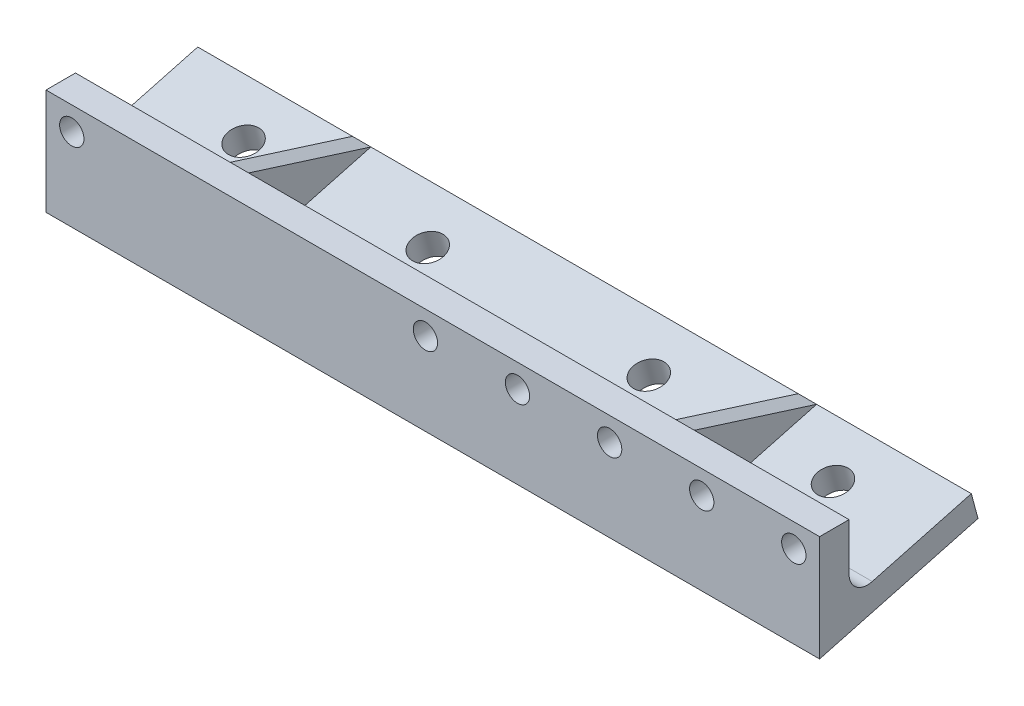
SolidWorks part; units mm, degrees
other "标注1"
sketch "草图25" plane through (-52, 30, -95) normal (-0.4172, 0.7166, -0.559) x (-0.8994, -0.2372, 0.3671)
other "标注2"
sketch "草图26" plane through (-52, 30, -95) normal (-0.4172, 0.7166, -0.559) x (-0.8994, -0.2372, 0.3671)
material "1060 合金"
ref_plane "前视基准面" through (0, 0, 0) normal (0, 0, 1) x (1, 0, 0)
ref_plane "上视基准面" through (0, 0, 0) normal (0, 1, 0) x (1, 0, 0)
ref_plane "右视基准面" through (0, 0, 0) normal (1, 0, 0) x (0, 0, -1)
sketch "草图1" plane through (0, 0, 0) normal (0, 1, 0) x (1, 0, 0)
  line L0 (0, 0) -> (170, 0) construction
  line L1 (170, 31.93) -> (170, -31.93)
  line L2 (15.8391, 73.3084) -> (162.1119, 41.7045)
  line L3 (15.8391, -73.3084) -> (162.1119, -41.7045)
  arc A0 (15.8391, 73.3084) -> (15.8391, -73.3084) centre (0, 0) ccw
  arc A1 (162.1119, -41.7045) -> (170, -31.93) centre (160, -31.93) ccw
  arc A2 (170, 31.93) -> (162.1119, 41.7045) centre (160, 31.93) ccw
  point P6 (170, 0)
  dimension "D1" = 150
  dimension "D4" = 20
  dimension "D5" = 20
  dimension "D2" = 170
  dimension "D3" = 63.86
extrude "凸台-拉伸1" add sketch "草图1" along normal blind 30
sketch "草图2" plane through (0, 30, 0) normal (0, 1, 0) x (1, 0, 0)
  circle A0 centre (0, 0) radius 44.45
  dimension "D1" = 88.9
extrude "切除-拉伸1" cut sketch "草图2" against normal blind 4
sketch "草图3" plane through (0, 26, 0) normal (0, 1, 0) x (1, 0, 0)
  line L0 (0, 0) -> (0, 90.3276) construction
  circle A0 centre (0, 0) radius 25.5
  circle A1 centre (0, 41) radius 2.25
  circle A2 centre (28.9914, 28.9914) radius 2.25
  circle A3 centre (41, 0) radius 2.25
  circle A4 centre (28.9914, -28.9914) radius 2.25
  circle A5 centre (0, -41) radius 2.25
  circle A6 centre (-28.9914, -28.9914) radius 2.25
  circle A7 centre (-41, 0) radius 2.25
  circle A8 centre (-28.9914, 28.9914) radius 2.25
  dimension "D1" = 51
  dimension "D3" = 4.5
  dimension "D2" = 41
  dimension "D4" = 8
extrude "切除-拉伸2" cut sketch "草图3" against normal through all contours A2 | A3 | A4 | A5 | A6 | A7 | A8 | A1 | A0
sketch "草图4" plane through (0, 30, 0) normal (0, 1, 0) x (1, 0, 0)
  line L0 (0, 0) -> (134, 0) construction
  line L1 (124, 18.5) -> (134, 18.5)
  line L2 (124, -18.5) -> (134, -18.5)
  arc A0 (134, -18.5) -> (134, 18.5) centre (134, 0) ccw
  arc A1 (124, 18.5) -> (124, -18.5) centre (124, 0) ccw
  dimension "D2" = 37
  dimension "D3" = 37
  dimension "D1" = 134
  dimension "D4" = 10
extrude "切除-拉伸3" cut sketch "草图4" against normal through all
sketch "草图5" plane through (0, 30, 0) normal (0, 1, 0) x (1, 0, 0)
  arc A0 (134, -18.5) -> (134, 18.5) centre (134, 0) ccw construction
  arc A1 (124, 18.5) -> (124, -18.5) centre (124, 0) ccw construction
  arc A2 (134, -18.5) -> (134, 18.5) centre (134, 0) ccw construction
  arc A3 (124, 18.5) -> (124, -18.5) centre (124, 0) ccw construction
  circle A4 centre (116.75, 25.5) radius 1.65
  circle A5 centre (141.25, 25.5) radius 1.65
  circle A6 centre (141.25, -25.5) radius 1.65
  circle A7 centre (116.75, -25.5) radius 1.65
  dimension "D1" = 3.3
  dimension "D2" = 3.3
  dimension "D3" = 3.3
  dimension "D4" = 3.3
  dimension "D7" = 25.5
  dimension "D5" = 7.25
  dimension "D6" = 25.5
  dimension "D8" = 7.25
  dimension "D9" = 7.25
extrude "切除-拉伸4" cut sketch "草图5" against normal through all
sketch "草图6" plane through (0, 30, 0) normal (0, 1, 0) x (1, 0, 0)
  line L0 (158, 42.5929) -> (158, -42.5929) construction
  line L2 (-52, 54.0463) -> (-52, -54.0463) construction
  line L6 (162.1119, 41.7045) -> (15.8391, 73.3084) construction
  line L7 (15.8391, -73.3084) -> (162.1119, -41.7045) construction
  line L8 (-52, 95) -> (-52, -95)
  line L9 (158, 95) -> (158, -95)
  line L10 (-52, 95) -> (158, 95)
  line L11 (-52, -95) -> (158, -95)
  line L15 (162.1119, 41.7045) -> (15.8391, 73.3084)
  line L16 (15.8391, -73.3084) -> (162.1119, -41.7045)
  line L17 (170, -31.93) -> (170, 31.93)
  line L18 (162.1119, 41.7045) -> (15.8391, 73.3084)
  line L19 (15.8391, -73.3084) -> (162.1119, -41.7045)
  line L20 (170, -31.93) -> (170, 31.93)
  arc A0 (15.8391, 73.3084) -> (15.8391, -73.3084) centre (0, 0) ccw construction
  arc A6 (170, 31.93) -> (162.1119, 41.7045) centre (160, 31.93) ccw
  arc A7 (15.8391, 73.3084) -> (15.8391, -73.3084) centre (0, 0) ccw
  arc A8 (162.1119, -41.7045) -> (170, -31.93) centre (160, -31.93) ccw
  arc A9 (170, 31.93) -> (162.1119, 41.7045) centre (160, 31.93) ccw
  arc A10 (15.8391, 73.3084) -> (15.8391, -73.3084) centre (0, 0) ccw
  arc A11 (162.1119, -41.7045) -> (170, -31.93) centre (160, -31.93) ccw
  point P8 (-52, 0)
  point P13 (158, 0)
  line M26 (162.1119, 41.7045) -> (15.8391, 73.3084)
  arc M27 (15.8391, 73.3084) -> (15.8391, -73.3084) centre (0, 0) ccw
  line M28 (15.8391, -73.3084) -> (162.1119, -41.7045)
  dimension "D3" = 190
  dimension "D1" = 210
  dimension "D2" = 52
  dimension "D4" = 190
  dimension "D5" = 0
extrude "凸台-拉伸2" add sketch "草图6" against normal blind 30 contours L10 L8 L9 M27 M26 | L8 L11 L9 M28 M27
sketch "草图7" plane through (0, 30, 0) normal (0, 1, 0) x (1, 0, 0)
  line L0 (-52, 54.0463) -> (-52, -54.0463)
  line L1 (158, 42.5929) -> (158, -42.5929)
  line L9 (162.1119, 41.7045) -> (158, 42.5929)
  line L10 (158, 42.5929) -> (158, 95)
  line L11 (158, 95) -> (-52, 95)
  line L12 (-52, 95) -> (-52, 54.0463)
  line L13 (-52, -54.0463) -> (-52, -95)
  line L14 (-52, -95) -> (158, -95)
  line L15 (158, -95) -> (158, -42.5929)
  line L16 (158, -42.5929) -> (162.1119, -41.7045)
  line L17 (170, -31.93) -> (170, 31.93)
  line L18 (162.1119, 41.7045) -> (158, 42.5929)
  line L21 (-52, 95) -> (-52, 54.0463)
  line L25 (158, -42.5929) -> (162.1119, -41.7045)
  line L26 (170, -31.93) -> (170, 31.93)
  arc A3 (170, 31.93) -> (162.1119, 41.7045) centre (160, 31.93) ccw
  arc A4 (-52, 54.0463) -> (-52, -54.0463) centre (0, 0) ccw
  arc A5 (162.1119, -41.7045) -> (170, -31.93) centre (160, -31.93) ccw
  arc A6 (170, 31.93) -> (162.1119, 41.7045) centre (160, 31.93) ccw
  arc A7 (-52, 54.0463) -> (-52, -54.0463) centre (0, 0) ccw
  arc A8 (162.1119, -41.7045) -> (170, -31.93) centre (160, -31.93) ccw
  arc M22 (170, 31.93) -> (162.1119, 41.7045) centre (160, 31.93) ccw
  line M23 (162.1119, 41.7045) -> (158, 42.5929)
  arc M27 (-52, 54.0463) -> (-52, -54.0463) centre (0, 0) ccw
  line M31 (158, -42.5929) -> (162.1119, -41.7045)
  arc M32 (162.1119, -41.7045) -> (170, -31.93) centre (160, -31.93) ccw
  line M33 (170, -31.93) -> (170, 31.93)
  dimension "D1" = 0
extrude "切除-拉伸5" cut sketch "草图7" against normal through all contours L0 M27 | L1 M23 M31 M32 M33 M22
sketch "草图9" plane through (-52, 0, 0) normal (-1, 0, 0) x (0, 0, 1)
  line L0 (-95, 20) -> (-60, 10.6218)
  line L1 (-95, 30) -> (95, 30) construction
  line L3 (-60, 10.6218) -> (-60, 30)
  line L5 (-95, 0) -> (-95, 30) construction
  line L7 (-95, 20) -> (-95, 30)
  line L8 (-95, 30) -> (-60, 30)
  dimension "D1" = 15
  dimension "D3" = 19.3782
  dimension "D4" = 35
  dimension "D5" = 10
extrude "切除-拉伸7" cut sketch "草图9" against normal through all contours L8 L3 L0 L7
sketch "草图8" plane through (-52, 0, 0) normal (-1, 0, 0) x (0, 0, 1)
  line L0 (0, 0) -> (52, 0)
  line L1 (-95, 0) -> (95, 0) construction
  line L2 (52, 0) -> (52, 17.3)
  line L3 (52, 17.3) -> (-52, 17.3)
  line L4 (-52, 17.3) -> (-52, 0)
  line L5 (-52, 0) -> (0, 0)
  line L6 (-60, 30) -> (95, 30) construction
  dimension "D1" = 52
  dimension "D2" = 52
  dimension "D3" = 12.7
sketch "草图10" plane through (-52, 0, 0) normal (-1, 0, 0) x (0, 0, 1)
  line L0 (-95, 12.7531) -> (-47.4049, 0) construction
  line L1 (-95, 0) -> (-95, 20) construction
  line L2 (-95, 0) -> (95, 0) construction
  line L3 (-95, 20) -> (-60, 10.6218) construction
  line L6 (-95, 12.7531) -> (-52, 1.2313)
  line L7 (-52, 1.2313) -> (-52, 0)
  line L8 (-95, 12.7531) -> (-95, 0)
  line L9 (-95, 0) -> (-52, 0)
  line L10 (-52, 17.3) -> (-52, 0) construction
  dimension "D1" = 7
extrude "切除-拉伸8" cut sketch "草图10" against normal through all
extrude "切除-拉伸9" cut sketch "草图8" against normal through all
fillet "圆角1" radius 5 1 edges at (53, 10.6218, -60)
sketch "草图11" plane through (-52, 0, 0) normal (-1, 0, 0) x (0, 0, 1)
  line L0 (-95, 12.7531) -> (-93.1883, 19.5145)
  line L1 (-95, 20) -> (-66.2941, 12.3083) construction
  line L2 (-93.1883, 19.5145) -> (-95, 20)
  line L3 (-95, 20) -> (-95, 12.7531)
extrude "切除-拉伸10" cut sketch "草图11" against normal through all
sketch "草图12" plane through (-52, 0, 0) normal (-1, 0, 0) x (0, 0, 1)
  line L0 (-93.1883, 19.5145) -> (-60, 30)
  line L10 (-93.1883, 19.5145) -> (-95, 12.7531)
  line L11 (-95, 12.7531) -> (-52, 1.2313)
  line L12 (-52, 1.2313) -> (-52, 17.3)
  line L13 (-52, 17.3) -> (52, 17.3)
  line L14 (52, 17.3) -> (52, 0)
  line L15 (52, 0) -> (95, 0)
  line L16 (95, 0) -> (95, 30)
  line L17 (95, 30) -> (-60, 30)
  line L18 (-60, 30) -> (-60, 17.1379)
  line L19 (-66.2941, 12.3083) -> (-93.1883, 19.5145)
  line L28 (-60, 30) -> (-60, 17.1379)
  line L29 (-66.2941, 12.3083) -> (-93.1883, 19.5145)
  arc A1 (-66.2941, 12.3083) -> (-60, 17.1379) centre (-65, 17.1379) ccw
  arc A2 (-66.2941, 12.3083) -> (-60, 17.1379) centre (-65, 17.1379) ccw
  dimension "D1" = 0
extrude "凸台-拉伸3" add sketch "草图12" against normal blind 5
sketch "草图13" plane through (158, 0, 0) normal (1, 0, 0) x (0, 0, -1)
  line L3 (66.2941, 12.3083) -> (93.1883, 19.5145)
  line L4 (93.1883, 19.5145) -> (60, 30)
  line L5 (60, 30) -> (60, 17.1379)
  line L6 (66.2941, 12.3083) -> (93.1883, 19.5145)
  line L7 (93.1883, 19.5145) -> (60, 30)
  line L8 (60, 30) -> (60, 17.1379)
  arc A1 (60, 17.1379) -> (66.2941, 12.3083) centre (65, 17.1379) ccw
  arc A2 (60, 17.1379) -> (66.2941, 12.3083) centre (65, 17.1379) ccw
  dimension "D1" = 0
extrude "凸台-拉伸4" add sketch "草图13" against normal blind 5
sketch "草图14" plane through (0, -5.0897, -1.3638) normal (0, 0.9659, 0.2588) x (1, 0, 0)
  line L0 (153, 67.2208) -> (153, 95.0637) construction
  line L3 (153, 95.0637) -> (-47, 95.0637) construction
  circle A0 centre (-27, 82.0637) radius 4.25
  circle A1 centre (23, 82.0637) radius 4.25
  circle A2 centre (83, 82.0637) radius 4.25
  circle A3 centre (133, 82.0637) radius 4.25
  dimension "D1" = 8.5
  dimension "D2" = 160
  dimension "D3" = 20
  dimension "D4" = 50
  dimension "D5" = 50
  dimension "D6" = 13
extrude "切除-拉伸11" cut sketch "草图14" against normal through all
sketch "草图16" plane through (-52, 0, 0) normal (-1, 0, 0) x (0, 0, 1)
  line L0 (-60, 30) -> (95, 30) construction
  line L1 (95, 0) -> (52, 0)
  line L2 (95, 0) -> (95, 30)
  line L3 (95, 30) -> (52, 30)
  line L4 (52, 0) -> (52, 30)
extrude "切除-拉伸12" cut sketch "草图16" against normal through all
ref_plane "基准面1" through (0, -11.8512, -3.1755) normal (0, -0.9659, -0.2588) x (-1, 0, 0)
sketch "草图18" plane through (0, 30, 0) normal (0, 1, 0) x (1, 0, 0)
  line L1 (-52, -52) -> (158, -52)
  line L2 (-52, -52) -> (-52, -57)
  line L3 (-52, -57) -> (158, -57)
  line L4 (158, -52) -> (158, -57)
  dimension "D1" = 5
extrude "凸台-拉伸7" add sketch "草图18" against normal up to surface (56.6355 mm away) up to plane "基准面1"
sketch "草图19" plane through (-52, 0, 0) normal (-1, 0, 0) x (0, 0, 1)
  line L0 (57, -27.9752) -> (90.1883, -36.868)
  line L1 (90.1883, -36.868) -> (92, -30.1065)
  line L2 (92, -30.1065) -> (57, -20.7283)
  line L3 (57, -27.9752) -> (57, 30) construction
  line L4 (57, -20.7283) -> (57, -27.9752)
  line L5 (52, -26.6355) -> (57, -27.9752) construction
  dimension "D1" = 7
  dimension "D2" = 40
extrude "凸台-拉伸8" add sketch "草图19" against normal up to surface (210 mm away) up to face at (158, 8.1654, -14.9098)
sketch "草图20" plane through (-52, 0, 0) normal (-1, 0, 0) x (0, 0, 1)
  line L0 (92, -30.1065) -> (57, -20.7283) construction
  line L1 (57, -20.7283) -> (57, 30) construction
  line L2 (92, -30.1065) -> (57, -20.7283)
  line L3 (57, -20.7283) -> (57, 30)
  line L4 (57, 30) -> (92, -30.1065)
extrude "凸台-拉伸9" add sketch "草图20" against normal blind 5
sketch "草图21" plane through (158, 0, 0) normal (1, 0, 0) x (0, 0, -1)
  line L3 (-57, 30) -> (-92, -30.1065)
  line L4 (-92, -30.1065) -> (-57, -20.7283)
  line L5 (-57, -20.7283) -> (-57, 30)
  line L6 (-57, 30) -> (-92, -30.1065)
  line L7 (-92, -30.1065) -> (-57, -20.7283)
  line L8 (-57, -20.7283) -> (-57, 30)
  dimension "D1" = 0
extrude "凸台-拉伸10" add sketch "草图21" against normal blind 5
sketch "草图22" plane through (0, -5.0897, -1.3638) normal (0, 0.9659, 0.2588) x (1, 0, 0)
  line L0 (-47, -96.6573) -> (-47, -47.2932) construction
  line L2 (153, -96.6573) -> (153, -60.4226) construction
  circle A0 centre (-27, -77.9363) radius 4.25
  circle A1 centre (23, -69.9363) radius 4.25
  circle A2 centre (83, -69.9363) radius 4.25
  circle A3 centre (133, -77.9363) radius 4.25
  circle A4 centre (133, 82.0637) radius 4.25 construction
  circle A5 centre (-27, 82.0637) radius 4.25 construction
  circle A6 centre (23, 82.0637) radius 4.25 construction
  circle A7 centre (83, 82.0637) radius 4.25 construction
  dimension "D1" = 8.5
  dimension "D7" = 152
  dimension "D6" = 152
  dimension "D8" = 50
  dimension "D4" = 160
  dimension "D5" = 160
  dimension "D2" = 20
  dimension "D3" = 20
  dimension "D9" = 50
extrude "切除-拉伸13" cut sketch "草图22" against normal through all
fillet "圆角2" radius 5 1 edges at (53, -20.7283, 57)
sketch "草图23" plane through (-52, 0, 0) normal (-1, 0, 0) x (0, 0, 1)
  line L0 (-52, 17.3) -> (-52, 40.5241)
  line L1 (-52, 17.3) -> (-52, -43.9123)
  line L2 (-52, -43.9123) -> (98.6729, -43.9123)
  line L3 (98.6729, -43.9123) -> (98.6729, 40.5241)
  line L4 (98.6729, 40.5241) -> (-52, 40.5241)
extrude "切除-拉伸14" cut sketch "草图23" against normal through all
sketch "草图24" plane through (0, 0, -60) normal (0, 0, -1) x (-1, 0, 0)
  line L0 (52, 30) -> (52, 1.2313) construction
  line L1 (-153, 30) -> (47, 30) construction
  circle A0 centre (45, 23.65) radius 3.3
  circle A1 centre (-151, 23.65) radius 3.3
  circle A2 centre (-126, 23.65) radius 3.3
  circle A3 centre (-101, 23.65) radius 3.3
  circle A4 centre (-76, 23.65) radius 3.3
  circle A5 centre (-51, 23.65) radius 3.3
  dimension "D8" = 6.6
  dimension "D1" = 7
  dimension "D2" = 25
  dimension "D3" = 25
  dimension "D4" = 25
  dimension "D5" = 25
  dimension "D6" = 7
  dimension "D7" = 6.35
ref_plane "基准面2" through (113.5, 0, 0) normal (1, 0, 0) x (0, 0, -1)
sketch "草图27" plane through (113.5, 0, 0) normal (1, 0, 0) x (0, 0, -1)
  line L3 (60, 30) -> (60, 17.1379)
  line L4 (93.1883, 19.5145) -> (60, 30)
  line L5 (66.2941, 12.3083) -> (93.1883, 19.5145)
  line L6 (60, 30) -> (60, 17.1379)
  line L7 (93.1883, 19.5145) -> (60, 30)
  line L8 (66.2941, 12.3083) -> (93.1883, 19.5145)
  arc A1 (60, 17.1379) -> (66.2941, 12.3083) centre (65, 17.1379) ccw
  arc A2 (60, 17.1379) -> (66.2941, 12.3083) centre (65, 17.1379) ccw
  dimension "D1" = 0
extrude "凸台-拉伸11" add sketch "草图27" along normal mid plane 5
sketch "草图29" plane through (153, 0, 0) normal (-1, 0, 0) x (0, 0, 1)
  line L3 (-60, 17.1379) -> (-60, 30)
  line L4 (-60, 30) -> (-93.1883, 19.5145)
  line L5 (-93.1883, 19.5145) -> (-66.2941, 12.3083)
  line L6 (-60, 17.1379) -> (-60, 30)
  line L7 (-60, 30) -> (-93.1883, 19.5145)
  line L8 (-93.1883, 19.5145) -> (-66.2941, 12.3083)
  arc A1 (-66.2941, 12.3083) -> (-60, 17.1379) centre (-65, 17.1379) ccw
  arc A2 (-66.2941, 12.3083) -> (-60, 17.1379) centre (-65, 17.1379) ccw
  dimension "D1" = 0
extrude "切除-拉伸16" cut sketch "草图29" against normal blind 5
extrude "切除-拉伸17" cut sketch "草图24" against normal through all
ref_plane "基准面3" through (-7.5, 0, 0) normal (-1, 0, 0) x (0, 0, 1)
sketch "草图30" plane through (-7.5, 0, 0) normal (-1, 0, 0) x (0, 0, 1)
  line L5 (-93.1883, 19.5145) -> (-66.2941, 12.3083)
  line L6 (-60, 30) -> (-93.1883, 19.5145)
  line L7 (-60, 26.2749) -> (-60, 30)
  line L8 (-60, 21.0251) -> (-60, 26.2749)
  line L9 (-60, 17.1379) -> (-60, 21.0251)
  line L10 (-93.1883, 19.5145) -> (-66.2941, 12.3083)
  line L11 (-60, 30) -> (-93.1883, 19.5145)
  line L12 (-60, 26.2749) -> (-60, 30)
  line L13 (-60, 21.0251) -> (-60, 26.2749)
  line L14 (-60, 17.1379) -> (-60, 21.0251)
  arc A1 (-66.2941, 12.3083) -> (-60, 17.1379) centre (-65, 17.1379) ccw
  arc A2 (-66.2941, 12.3083) -> (-60, 17.1379) centre (-65, 17.1379) ccw
  dimension "D1" = 0
extrude "凸台-拉伸12" add sketch "草图30" along normal mid plane 5
sketch "草图31" plane through (-47, 0, 0) normal (1, 0, 0) x (0, 0, -1)
  line L5 (66.2941, 12.3083) -> (93.1883, 19.5145)
  line L6 (93.1883, 19.5145) -> (60, 30)
  line L7 (60, 30) -> (60, 26.2749)
  line L8 (60, 26.2749) -> (60, 21.0251)
  line L9 (60, 21.0251) -> (60, 17.1379)
  line L10 (66.2941, 12.3083) -> (93.1883, 19.5145)
  line L11 (93.1883, 19.5145) -> (60, 30)
  line L12 (60, 30) -> (60, 26.2749)
  line L13 (60, 26.2749) -> (60, 21.0251)
  line L14 (60, 21.0251) -> (60, 17.1379)
  arc A1 (60, 17.1379) -> (66.2941, 12.3083) centre (65, 17.1379) ccw
  arc A2 (60, 17.1379) -> (66.2941, 12.3083) centre (65, 17.1379) ccw
  dimension "D1" = 0
extrude "切除-拉伸18" cut sketch "草图31" against normal blind 5
